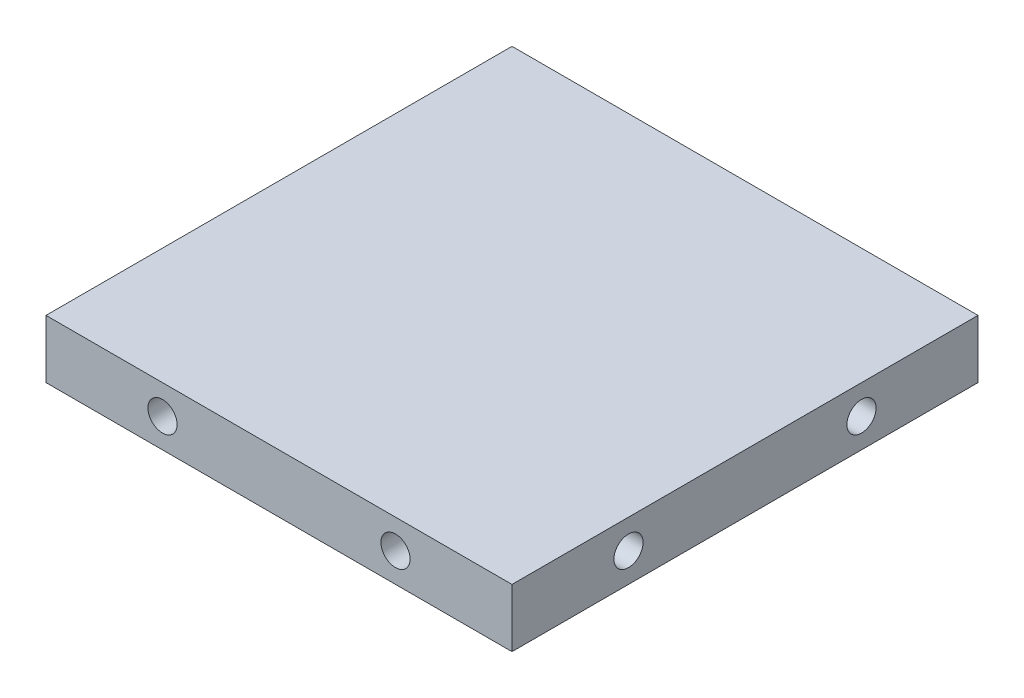
SolidWorks part; units mm, degrees
ref_plane "Front Plane" through (0, 0, 0) normal (0, 0, 1) x (1, 0, 0)
ref_plane "Top Plane" through (0, 0, 0) normal (0, 1, 0) x (1, 0, 0)
ref_plane "Right Plane" through (0, 0, 0) normal (1, 0, 0) x (0, 0, -1)
sketch "Sketch1" plane through (0, 0, 0) normal (0, 1, 0) x (1, 0, 0)
  line L1 (-20, -20) -> (20, -20)
  line L2 (-20, -20) -> (-20, 20)
  line L3 (-20, 20) -> (20, 20)
  line L4 (20, -20) -> (20, 20)
  line L5 (-20, -20) -> (20, 20) construction
  line L6 (-20, 20) -> (20, -20) construction
  point P0 (0, 0)
  dimension "D1" = 40
  dimension "D2" = 40
extrude "Boss-Extrude1" add sketch "Sketch1" along normal blind 5
sketch "Sketch2" plane through (0, 0, 20) normal (0, 0, 1) x (1, 0, 0)
  circle A0 centre (-10, 2.5) radius 1.25
  circle A1 centre (10, 2.5) radius 1.25
extrude "Cut-Extrude1" cut sketch "Sketch2" against normal blind 5
pattern_circular "CirPattern1" count 4 every 90 about axis through (0, 0, 0) along (0, 1, 0) of "Cut-Extrude1"
